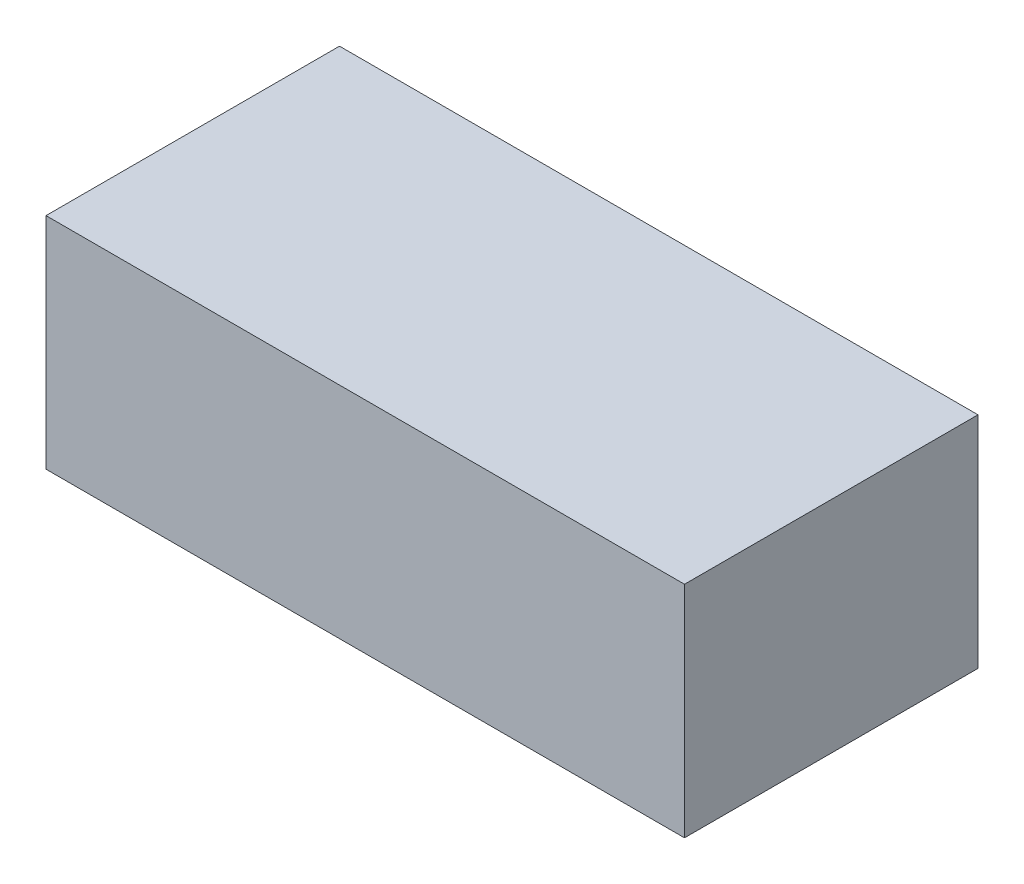
SolidWorks part; units mm, degrees
ref_plane "Front Plane" through (0, 0, 0) normal (0, 0, 1) x (1, 0, 0)
ref_plane "Top Plane" through (0, 0, 0) normal (0, 1, 0) x (1, 0, 0)
ref_plane "Right Plane" through (0, 0, 0) normal (1, 0, 0) x (0, 0, -1)
sketch "Sketch1" plane through (0, 0, 0) normal (0, 1, 0) x (1, 0, 0)
  line L0 (-32.85, 15.1) -> (32.85, 15.1)
  line L1 (-32.25, 14.5) -> (32.25, 14.5)
  line L2 (-32.25, 14.5) -> (-32.25, -14.5)
  line L3 (-32.25, -14.5) -> (32.25, -14.5)
  line L4 (32.25, 14.5) -> (32.25, -14.5)
  line L5 (-32.25, 14.5) -> (32.25, -14.5) construction
  line L6 (-32.25, -14.5) -> (32.25, 14.5) construction
  line L7 (32.85, 15.1) -> (32.85, -15.1)
  line L8 (-32.85, -15.1) -> (32.85, -15.1)
  line L9 (-32.85, 15.1) -> (-32.85, -15.1)
  point P0 (0, 0)
  dimension "D1" = 29
  dimension "D2" = 64.5
  dimension "D3" = 0.6
extrude "Boss-Extrude1" add sketch "Sketch1" along normal blind 22
sketch "Sketch2" plane through (0, 22, 0) normal (0, 1, 0) x (1, 0, 0)
  line L1 (32.85, -15.1) -> (-32.85, -15.1)
  line L2 (32.85, -15.1) -> (32.85, 15.1)
  line L3 (32.85, 15.1) -> (-32.85, 15.1)
  line L4 (-32.85, -15.1) -> (-32.85, 15.1)
  line L5 (32.85, -15.1) -> (-32.85, 15.1) construction
  line L6 (32.85, 15.1) -> (-32.85, -15.1) construction
  point P0 (0, 0)
extrude "Boss-Extrude2" add sketch "Sketch2" along normal blind 0.6
sketch "Sketch3" plane through (0, 0, -15.1) normal (0, 0, -1) x (-1, 0, 0)
  line L0 (-32.85, 0) -> (32.85, 0) construction
  line L1 (-30, 0) -> (30, 0)
  line L2 (-30, 0) -> (-30, 15)
  line L3 (-30, 15) -> (30, 15)
  line L4 (30, 0) -> (30, 15)
  line L5 (0, 15) -> (0, 0) construction
  dimension "D1" = 60
  dimension "D2" = 15
extrude "Cut-Extrude1" cut sketch "Sketch3" against normal blind 10.6
chamfer "Chamfer1" distance 1.5 angle 45 8 edges at (-32.25, 22, 0) (-32.25, 11, 14.5) (0, 22, 14.5) (32.25, 11, 14.5) (32.25, 22, 0) (-32.25, 11, -14.5) (0, 22, -14.5) (32.25, 11, -14.5)
